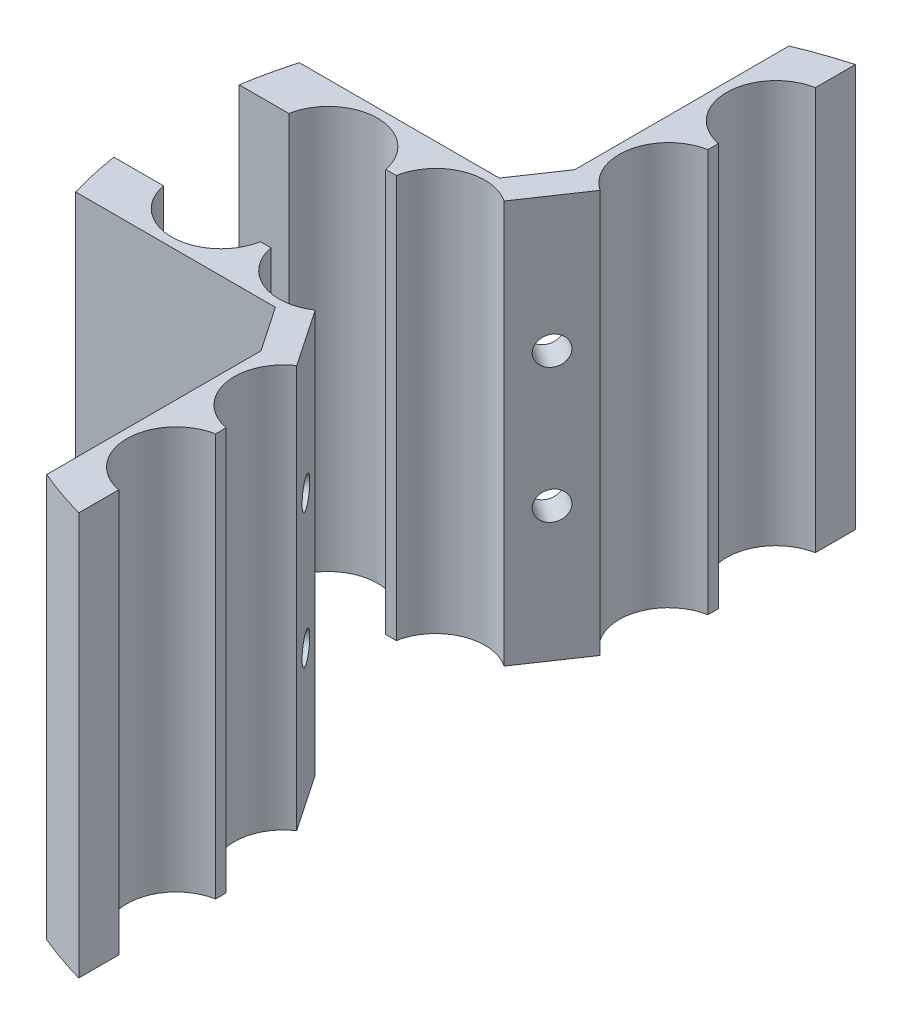
SolidWorks part; units mm, degrees
ref_plane "Front Plane" through (0, 0, 0) normal (0, 0, 1) x (1, 0, 0)
ref_plane "Top Plane" through (0, 0, 0) normal (0, 1, 0) x (1, 0, 0)
ref_plane "Right Plane" through (0, 0, 0) normal (1, 0, 0) x (0, 0, -1)
sketch "Sketch1" plane through (0, 0, 0) normal (0, 1, 0) x (1, 0, 0)
  line L1 (0, 45) -> (45, 45)
  line L2 (0, 45) -> (0, -45)
  line L3 (0, -45) -> (45, -45)
  line L4 (45, 45) -> (45, -45)
  circle A0 centre (0, 0) radius 45
extrude "Boss-Extrude2" add sketch "Sketch1" along normal blind 45 contours L2 A0
sketch "Sketch2" plane through (0, 45, 0) normal (0, 1, 0) x (1, 0, 0)
  line L0 (-24.75, 0) -> (24.75, 0) construction
  circle A0 centre (-11, -21.5) radius 5.5
  circle A1 centre (-11, -33.5) radius 5.5
  circle A2 centre (-21.5, -6) radius 5.5
  circle A3 centre (-33.5, -6) radius 5.5
  circle A4 centre (-11, 33.5) radius 5.5
  circle A5 centre (-11, 21.5) radius 5.5
  circle A6 centre (-21.5, 6) radius 5.5
  circle A7 centre (-33.5, 6) radius 5.5
extrude "Cut-Extrude1" cut sketch "Sketch2" against normal blind 45
sketch "Sketch3" plane through (0, 45, 0) normal (0, 1, 0) x (1, 0, 0)
  line L0 (-24.75, 0) -> (24.75, 0) construction
  line L1 (0, 0) -> (-47.201, 0)
  line L2 (0, -6) -> (0, 6)
  line L3 (0, 6) -> (-47.201, 6)
  line L4 (-47.201, -6) -> (-47.201, 6)
  line L5 (0, 0) -> (-11, 0)
  line L6 (0, -47.8327) -> (0, 47.8327)
  line L7 (0, 47.8327) -> (-11, 47.8327)
  line L8 (-11, -47.8327) -> (-11, 47.8327)
  line L9 (0, -6) -> (-47.201, -6)
  line L10 (0, -47.8327) -> (-11, -47.8327)
  circle M9 centre (-11, 33.5) radius 5.5
  circle M10 centre (-33.5, -6) radius 5.5
  circle M11 centre (-21.5, -6) radius 5.5
  circle M12 centre (-11, -33.5) radius 5.5
  circle M13 centre (-11, 21.5) radius 5.5
  circle M14 centre (-21.5, 6) radius 5.5
  circle M15 centre (-33.5, 6) radius 5.5
  circle M16 centre (-11, -21.5) radius 5.5
  line M17 (0, -45) -> (0, 45)
  arc M18 (0, 45) -> (0, -45) centre (0, 0) ccw
extrude "Cut-Extrude2" cut sketch "Sketch3" against normal blind 45 contours L8 L3 M17 M18 M9 M13 | L9 L8 M17 M16 M12 M18 | L9 L8 L1 M18 M10 M11 | L1 L8 L3 M14 M15 M18 | L8 L1 L3 M17 | L9 L1 L8 M17
sketch "Sketch4" plane through (0, 45, 0) normal (0, 1, 0) x (1, 0, 0)
  line L0 (-21.5, 6) -> (-11, 21.5)
  line L1 (-11, 21.5) -> (-11, 6)
  line L2 (-11, 6) -> (-11, 16) construction
  line L3 (-11, 6) -> (-21.5, 6)
  line L4 (-24.75, 0) -> (24.75, 0) construction
  line L5 (-11, 6) -> (-48.0177, 6)
  line L6 (-11, 6) -> (-11, 7)
  line L7 (-11, 7) -> (-48.0177, 7)
  line L8 (-48.0177, 6) -> (-48.0177, 7)
  line L9 (-11, 6) -> (-12, 6)
  line L10 (-11, 6) -> (-11, 46.6118)
  line L11 (-11, 46.6118) -> (-12, 46.6118)
  line L12 (-12, 6) -> (-12, 46.6118)
  line L13 (-11, -46.6118) -> (-12, -46.6118)
  line L14 (-12, -6) -> (-12, -46.6118)
  line L15 (-11, -6) -> (-12, -6)
  line L16 (-11, -6) -> (-11, -46.6118)
  line L17 (-11, -21.5) -> (-11, -6)
  line L18 (-21.5, -6) -> (-11, -21.5)
  line L19 (-11, -6) -> (-21.5, -6)
  line L20 (-11, -7) -> (-48.0177, -7)
  line L21 (-48.0177, -6) -> (-48.0177, -7)
  line L22 (-11, -6) -> (-48.0177, -6)
  line L23 (-11, -6) -> (-11, -7)
extrude "Cut-Extrude3" cut sketch "Sketch4" against normal blind 45 contours L9 L12 L11 L10 | L3 L0 L1 | L6 L7 L8 L5 | L22 L21 L20 L23 | L16 L13 L14 L15 | L19 L18 L17
sketch "Sketch5" plane through (0, 45, 0) normal (0, 1, 0) x (1, 0, 0)
  line L0 (-21.5, 8.952) -> (-13, 21.5)
  line L1 (-11, 21.5) -> (-13, 21.5)
  line L2 (-21.5, 6) -> (-21.5, 8.952)
  line L3 (-21.5, 11.5) -> (-21.5, 12.5)
  line L4 (-21.5, 12.5) -> (-19.0966, 12.5)
  line L5 (-21.5, 12.5) -> (-43.229, 12.5)
  line L6 (-16.5, 21.5) -> (-17.5, 21.5)
  line L7 (-17.5, 21.5) -> (-17.5, 14.8569)
  line L8 (-17.5, 21.5) -> (-17.5, 41.4578)
  line L9 (-17.8487, 0) -> (17.8487, 0) construction
  line L10 (-21.5, -12.5) -> (-19.0966, -12.5)
  line L11 (-21.5, -12.5) -> (-43.229, -12.5)
  line L12 (-21.5, -8.952) -> (-13, -21.5)
  line L13 (-17.5, -21.5) -> (-17.5, -14.8569)
  line L14 (-17.5, -21.5) -> (-17.5, -41.4578)
  line L15 (-43.229, -41.4578) -> (-43.229, -12.5)
  line L16 (-43.229, -41.4578) -> (-17.5, -41.4578)
  line L17 (-43.229, 12.5) -> (-43.229, 41.4578)
  line L18 (-43.229, 41.4578) -> (-17.5, 41.4578)
  line L19 (-21.5, 8.952) -> (-22.7419, 9.7933)
  line L20 (-22.7419, 9.7933) -> (-14.1299, 22.5066)
  line L21 (-14.1299, 22.5066) -> (-13, 21.5)
  line L22 (-18.6899, -13.1004) -> (-19.9318, -13.9417)
  line L23 (-19.9318, -13.9417) -> (-22.9879, -9.4301)
  line L24 (-19.9318, -13.9417) -> (-16.4268, -19.1158)
  arc A0 (-18.4153, 10.5536) -> (-26.9083, 7) centre (-21.5, 6) ccw construction
  arc A1 (-12, 43.3705) -> (-44.4522, 7) centre (0, 0) ccw construction
  arc A2 (-12, 26.9083) -> (-14.0847, 16.9464) centre (-11, 21.5) ccw construction
  arc M14 (-12, 43.3705) -> (-44.4522, 7) centre (0, 0) ccw
extrude "Cut-Extrude4" cut sketch "Sketch5" against normal blind 45 contours L7 L8 L5 L4 L0 M14 | L15 L16 L14 L13 L12 L10 L11 | L18 L17 M14
sketch "Sketch8" plane through (-17.5232, 0, 11.8705) normal (0.8279, 0, -0.5608) x (-0.5608, 0, -0.8279)
  circle A1 centre (-2.2701, 15) radius 1.6
  circle A2 centre (-2.2701, 30) radius 1.6
extrude "Cut-Extrude5" cut sketch "Sketch8" against normal blind 45
sketch "Sketch9" plane through (-17.5232, 0, -11.8705) normal (0.8279, 0, 0.5608) x (0.5608, 0, -0.8279)
  circle A0 centre (2.2701, 30) radius 1.6
  circle A1 centre (2.2701, 15) radius 1.6
extrude "Cut-Extrude6" cut sketch "Sketch9" against normal blind 45
